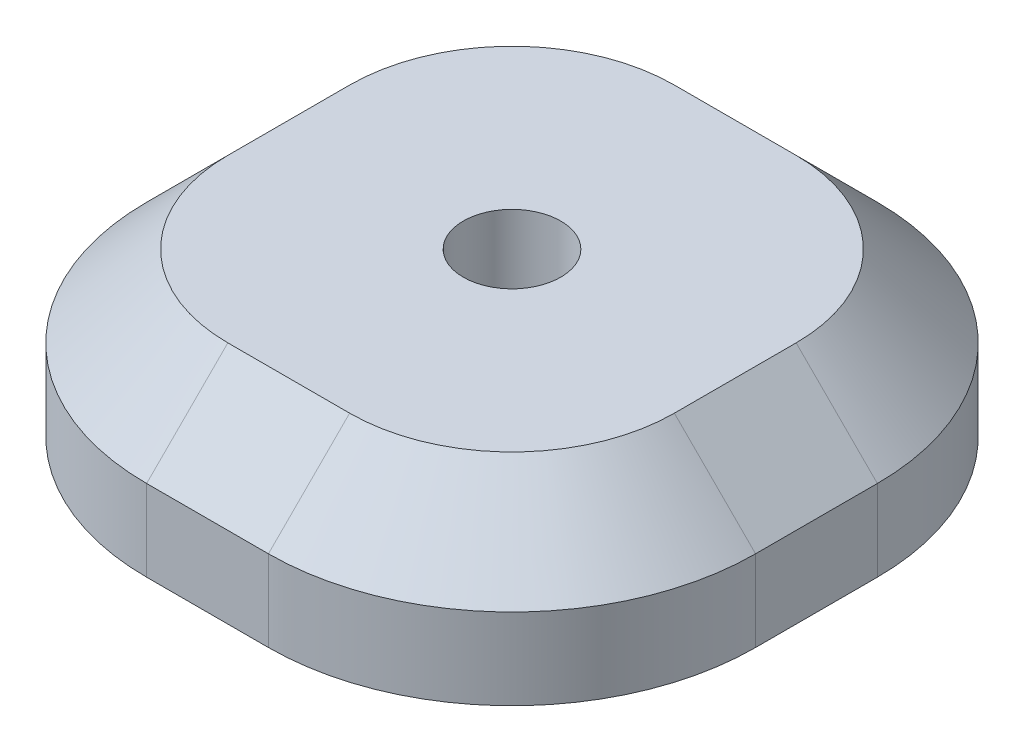
SolidWorks part; units mm, degrees
ref_plane "Alzado" through (0, 0, 0) normal (0, 0, 1) x (1, 0, 0)
ref_plane "Planta" through (0, 0, 0) normal (0, 1, 0) x (1, 0, 0)
ref_plane "Vista lateral" through (0, 0, 0) normal (1, 0, 0) x (0, 0, -1)
sketch "Croquis1" plane through (0, 0, 0) normal (0, 1, 0) x (1, 0, 0)
  line L1 (7.5, -37.5) -> (-7.5, -37.5)
  line L2 (37.5, -7.5) -> (37.5, 7.5)
  line L3 (7.5, 37.5) -> (-7.5, 37.5)
  line L4 (-37.5, -7.5) -> (-37.5, 7.5)
  line L5 (37.5, -37.5) -> (-37.5, 37.5) construction
  line L6 (37.5, 37.5) -> (-37.5, -37.5) construction
  arc A0 (37.5, 7.5) -> (7.5, 37.5) centre (7.5, 7.5) ccw
  arc A1 (7.5, -37.5) -> (37.5, -7.5) centre (7.5, -7.5) ccw
  arc A2 (-7.5, -37.5) -> (-37.5, -7.5) centre (-7.5, -7.5) cw
  arc A3 (-7.5, 37.5) -> (-37.5, 7.5) centre (-7.5, 7.5) ccw
  point P0 (0, 0)
  dimension "D2" = 30
extrude "Saliente-Extruir1" add sketch "Croquis1" along normal blind 20
chamfer "Chaflán1" distance 10 angle 45 8 edges at (-28.7132, 20, -28.7132) (0, 20, -37.5) (28.7132, 20, -28.7132) (37.5, 20, 0) (28.7132, 20, 28.7132) (0, 20, 37.5) (-28.7132, 20, 28.7132) (-37.5, 20, 0)
sketch "Croquis2" [suppressed] plane through (0, 20, 0) normal (0, 1, 0) x (1, 0, 0)
  line L1 (12.5, -12.5) -> (-12.5, -12.5) construction
  line L2 (12.5, -12.5) -> (12.5, 12.5) construction
  line L3 (12.5, 12.5) -> (-12.5, 12.5) construction
  line L4 (-12.5, -12.5) -> (-12.5, 12.5) construction
  line L5 (12.5, -12.5) -> (-12.5, 12.5) construction
  line L6 (12.5, 12.5) -> (-12.5, -12.5) construction
  line L7 (12.5, -12.5) -> (-12.5, -12.5) construction
  line L8 (12.5, -12.5) -> (12.5, 12.5) construction
  line L9 (12.5, 12.5) -> (-12.5, 12.5) construction
  line L10 (-12.5, -12.5) -> (-12.5, 12.5) construction
  line L11 (12.5, -12.5) -> (-12.5, 12.5) construction
  line L12 (12.5, 12.5) -> (-12.5, -12.5) construction
  point P0 (0, 0)
  point P6 (0, 0)
sketch "Croquis7" [suppressed] plane through (0, 0, 0) normal (0, -1, 0) x (1, 0, 0)
  line L0 (12.5, 12.5) -> (12.5, -12.5) construction
  line L1 (12.5, -12.5) -> (-12.5, -12.5) construction
  line L2 (-12.5, 12.5) -> (-12.5, -12.5) construction
  line L3 (12.5, 12.5) -> (-12.5, 12.5) construction
  line L4 (12.5, 12.5) -> (12.5, -12.5) construction
  line L5 (12.5, -12.5) -> (-12.5, -12.5) construction
  line L6 (-12.5, 12.5) -> (-12.5, -12.5) construction
  line L7 (12.5, 12.5) -> (-12.5, 12.5) construction
hole_wizard "Taladro de margen para M102" [suppressed] positions "Croquis3D4" profile "Croquis8" hole size "M10" standard "ISO"
sketch3d "Croquis3D4" [suppressed]
  point P0 (-12.5, 0, 12.5)
  point P3 (12.5, 0, 12.5)
  point P6 (12.5, 0, -12.5)
  point P9 (-12.5, 0, -12.5)
sketch "Croquis8" plane through (-12.5, 0, 12.5) normal (1, 0, 0) x (0, 0, -1)
  line L0 (0, 0) -> (0, 13.6052)
  line L1 (0, 13.6052) -> (6, 10)
  line L2 (6, 10) -> (6, 0)
  line L5 (6, 0) -> (0, 0)
  line L10 (0, 13.6052) -> (-6, 10) construction
  line L11 (0, -6.35) -> (0, 107.95) construction
  dimension "Diámetro de taladro" = 12
  dimension "Profundidad de taladro" = 10
  dimension "Ángulo de perforador" = 118
hole_wizard "Taladro de margen para M101" [suppressed] positions "Croquis3D1" profile "Croquis3" hole size "M10" standard "ISO"
sketch3d "Croquis3D1" [suppressed]
  point P0 (-12.5, 20, -12.5)
  point P3 (12.5, 20, -12.5)
  point P6 (-12.5, 20, 12.5)
  point P9 (12.5, 20, 12.5)
sketch "Croquis3" plane through (-12.5, 20, -12.5) normal (1, 0, 0) x (0, 0, 1)
  line L0 (0, 0) -> (0, 13.6052)
  line L1 (0, 13.6052) -> (6, 10)
  line L2 (6, 10) -> (6, 0)
  line L5 (6, 0) -> (0, 0)
  line L10 (0, 13.6052) -> (-6, 10) construction
  line L11 (0, -6.35) -> (0, 107.95) construction
  dimension "Diámetro de taladro" = 12
  dimension "Profundidad de taladro" = 10
  dimension "Ángulo de perforador" = 118
sketch "Croquis9" plane through (0, 0, 0) normal (0, -1, 0) x (1, 0, 0)
  line L1 (12.5, -12.5) -> (-12.5, -12.5) construction
  line L2 (12.5, -12.5) -> (12.5, 12.5) construction
  line L3 (12.5, 12.5) -> (-12.5, 12.5) construction
  line L4 (-12.5, -12.5) -> (-12.5, 12.5) construction
  line L5 (12.5, -12.5) -> (-12.5, 12.5) construction
  line L6 (12.5, 12.5) -> (-12.5, -12.5) construction
  point P0 (0, 0)
hole_wizard "Taladro de margen para M103" positions "Croquis3D5" profile "Croquis10" hole size "M10" standard "ISO"
sketch3d "Croquis3D5"
  point P0 (-12.5, 0, 12.5)
  point P3 (12.5, 0, 12.5)
  point P6 (12.5, 0, -12.5)
  point P9 (-12.5, 0, -12.5)
sketch "Croquis10" plane through (-12.5, 0, 12.5) normal (1, 0, 0) x (0, 0, -1)
  line L0 (0, 0) -> (0, 13.6052)
  line L1 (0, 13.6052) -> (6, 10)
  line L2 (6, 10) -> (6, 0)
  line L5 (6, 0) -> (0, 0)
  line L10 (0, 13.6052) -> (-6, 10) construction
  line L11 (0, -6.35) -> (0, 107.95) construction
  dimension "Diámetro de taladro" = 12
  dimension "Profundidad de taladro" = 10
  dimension "Ángulo de perforador" = 118
sketch "Croquis13" plane through (0, 20, 0) normal (0, 1, 0) x (1, 0, 0)
  point P0 (0, 0)
hole_wizard "Taladro de margen para M104" positions "Croquis3D8" profile "Croquis15" hole size "M10" standard "ISO"
sketch3d "Croquis3D8"
  point P0 (0, 20, 0)
sketch "Croquis15" plane through (0, 20, 0) normal (1, 0, 0) x (0, 0, 1)
  line L0 (0, 0) -> (0, 13.6052)
  line L1 (0, 13.6052) -> (6, 10)
  line L2 (6, 10) -> (6, 0)
  line L5 (6, 0) -> (0, 0)
  line L10 (0, 13.6052) -> (-6, 10) construction
  line L11 (0, -6.35) -> (0, 107.95) construction
  dimension "Diámetro de taladro" = 12
  dimension "Profundidad de taladro" = 10
  dimension "Ángulo de perforador" = 118
equation "\"A\" = 75mm"
equation "\"B\" = 0mm"
equation "\"C\" = 25mm"
equation "\"D\"= 20mm"
equation "\"D1@Croquis1\"=\"A\""
equation "\"D1@Saliente-Extruir1\"=\"D\""
equation "\"D1@Croquis2\"=\"C\""
equation "\"D2@Croquis2\"=\"B\""
equation "\"D1@Croquis9\"=\"C\""
